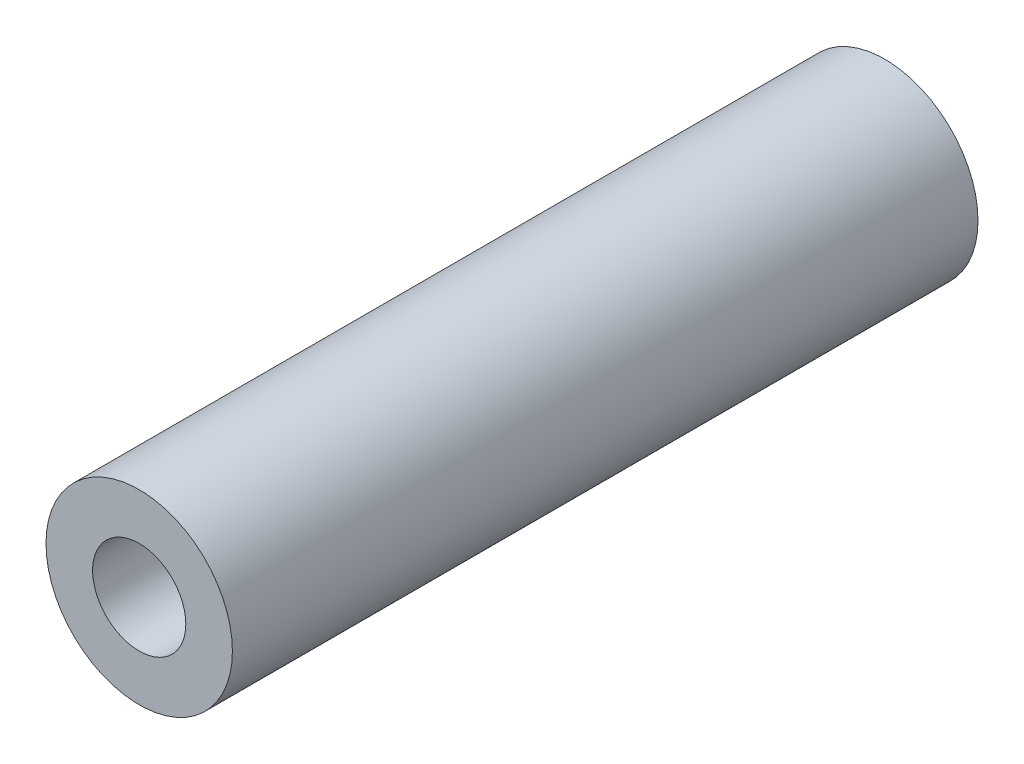
SolidWorks part; units mm, degrees
material "6061 Alloy"
ref_plane "Front Plane" through (0, 0, 0) normal (0, 0, 1) x (1, 0, 0)
ref_plane "Top Plane" through (0, 0, 0) normal (0, 1, 0) x (1, 0, 0)
ref_plane "Right Plane" through (0, 0, 0) normal (1, 0, 0) x (0, 0, -1)
sketch "Sketch1" plane through (0, 0, 0) normal (0, 0, 1) x (1, 0, 0)
  circle A0 centre (0, 0) radius 2.5
  dimension "D1" = 5
extrude "Boss-Extrude1" add sketch "Sketch1" along normal mid plane 20 contours A0
hole_wizard "M3x0.5 Tapped Hole1" positions "Sketch2" profile "Sketch3" tap size "M3x0.5" standard "ANSI Metric"
sketch "Sketch2" plane through (0, 0, 10) normal (0, 0, 1) x (1, 0, 0)
  point P0 (0, 0)
sketch "Sketch3" plane through (0, 0, 10) normal (1, 0, 0) x (0, -1, 0)
  line L0 (0, 0) -> (0, 10.7511)
  line L1 (0, 10.7511) -> (1.25, 10)
  line L2 (1.25, 10) -> (1.25, 0)
  line L5 (1.25, 0) -> (0, 0)
  line L10 (0, 10.7511) -> (-1.25, 10) construction
  line L11 (0, -6.35) -> (0, 107.95) construction
  dimension "Tap Drill Dia." = 2.5
  dimension "Tap Drill Depth" = 10
  dimension "Drill Angle" = 118
mirror "Mirror1" about plane through (0, 0, 0) normal (0, 0, 1) of "M3x0.5 Tapped Hole1"
